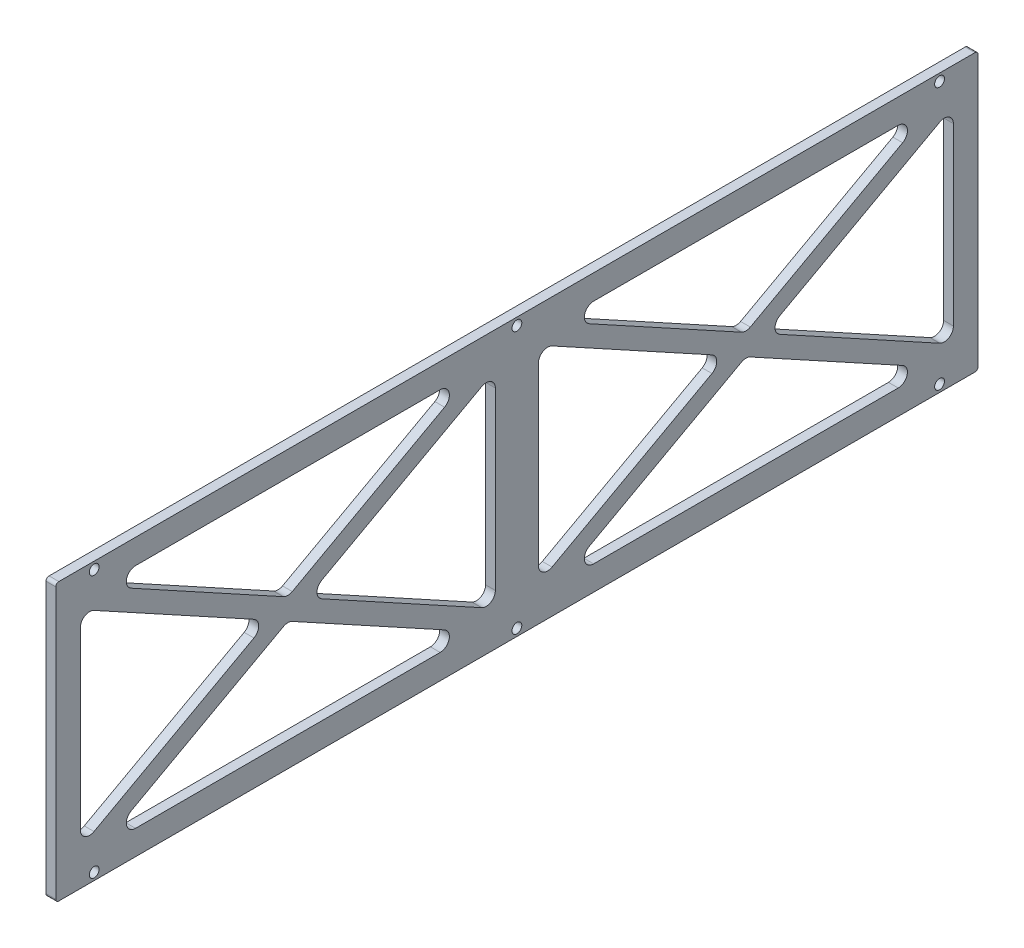
SolidWorks part; units mm, degrees
material "6061 Alloy"
ref_plane "Front Plane" through (0, 0, 0) normal (0, 0, 1) x (1, 0, 0)
ref_plane "Top Plane" through (0, 0, 0) normal (0, 1, 0) x (1, 0, 0)
ref_plane "Right Plane" through (0, 0, 0) normal (1, 0, 0) x (0, 0, -1)
sketch "Sketch2" plane through (0, 0, 0) normal (1, 0, 0) x (0, 0, -1)
  line L1 (-150, -45) -> (150, -45)
  line L2 (-150, -45) -> (-150, 45)
  line L3 (-150, 45) -> (150, 45)
  line L4 (150, -45) -> (150, 45)
  line L5 (-150, -45) -> (150, 45) construction
  line L6 (-150, 45) -> (150, -45) construction
  point P0 (0, 0)
  dimension "D1" = 300
  dimension "D2" = 90
extrude "Boss-Extrude1" add sketch "Sketch2" along normal blind 3.175
sketch "Sketch4" plane through (3.175, 0, 0) normal (1, 0, 0) x (0, 0, -1)
  line L0 (-150, 0) -> (-142, 0) construction
  line L1 (-142, -37) -> (-7, -37) construction
  line L2 (-142, -37) -> (-142, 37) construction
  line L3 (-142, 37) -> (-7, 37) construction
  line L4 (-7, -37) -> (-7, 37) construction
  line L5 (-142, -37) -> (-7, 37) construction
  line L6 (-142, 37) -> (-7, -37) construction
  line L7 (7, -37) -> (142, -37) construction
  line L8 (7, -37) -> (7, 37) construction
  line L9 (7, 37) -> (142, 37) construction
  line L10 (142, -37) -> (142, 37) construction
  line L11 (7, -37) -> (142, 37) construction
  line L12 (7, 37) -> (142, -37) construction
  line L13 (-150, 45) -> (-150, -45) construction
  line L14 (142, 0) -> (150, 0) construction
  line L15 (150, -45) -> (150, 45) construction
  line L17 (-143.442, 34.3693) -> (-8.442, -39.6307) construction
  line L18 (-142, 37) -> (-142, 45) construction
  line L19 (150, 45) -> (-150, 45) construction
  line L20 (-140.558, -39.6307) -> (-5.558, 34.3693) construction
  line L21 (-140.558, 39.6307) -> (-5.558, -34.3693) construction
  line L22 (-143.442, -34.3693) -> (-8.442, 39.6307) construction
  line L23 (-135.7587, 37) -> (-13.2413, 37)
  line L24 (-7, 33.5789) -> (-7, -33.5789)
  line L25 (-13.2413, -37) -> (-135.7587, -37)
  line L26 (-142, -33.5789) -> (-142, 33.5789)
  line L27 (-142, 33.5789) -> (-80.7413, 0)
  line L28 (-80.7413, 0) -> (-142, -33.5789)
  line L29 (-135.7587, -37) -> (-74.5, -3.4211)
  line L30 (-74.5, -3.4211) -> (-13.2413, -37)
  line L31 (-7, -33.5789) -> (-68.2587, 0)
  line L32 (-68.2587, 0) -> (-7, 33.5789)
  line L33 (-13.2413, 37) -> (-74.5, 3.4211)
  line L34 (-74.5, 3.4211) -> (-135.7587, 37)
  line L35 (5.558, 34.3693) -> (140.558, -39.6307) construction
  line L36 (8.442, -39.6307) -> (143.442, 34.3693) construction
  line L37 (8.442, 39.6307) -> (143.442, -34.3693) construction
  line L38 (5.558, -34.3693) -> (140.558, 39.6307) construction
  line L39 (135.7587, 37) -> (13.2413, 37)
  line L40 (13.2413, 37) -> (74.5, 3.4211)
  line L41 (74.5, 3.4211) -> (135.7587, 37)
  line L42 (142, 33.5789) -> (80.7413, 0)
  line L43 (80.7413, 0) -> (142, -33.5789)
  line L44 (142, -33.5789) -> (142, 33.5789)
  line L45 (135.7587, -37) -> (74.5, -3.4211)
  line L46 (74.5, -3.4211) -> (13.2413, -37)
  line L47 (13.2413, -37) -> (135.7587, -37)
  line L48 (7, -33.5789) -> (68.2587, 0)
  line L49 (68.2587, 0) -> (7, 33.5789)
  line L50 (7, 33.5789) -> (7, -33.5789)
  point P0 (-74.5, 0)
  point P5 (74.5, 0)
  dimension "D1" = 8
  dimension "D6" = 135
  dimension "D7" = 135
  dimension "D2" = 3
  dimension "D3" = 3
  dimension "D4" = 3
  dimension "D5" = 3
extrude "Cut-Extrude2" cut sketch "Sketch4" against normal through all
sketch "Sketch10" plane through (3.175, 0, 0) normal (1, 0, 0) x (0, 0, -1)
  line L0 (150, 45) -> (-150, 45) construction
  line L1 (-137.5, -42.6187) -> (137.5, -42.6187) construction
  line L2 (-137.5, -42.6187) -> (-137.5, 42.6187) construction
  line L3 (-137.5, 42.6187) -> (137.5, 42.6187) construction
  line L4 (137.5, -42.6187) -> (137.5, 42.6187) construction
  line L5 (-137.5, -42.6187) -> (137.5, 42.6187) construction
  line L6 (-137.5, 42.6187) -> (137.5, -42.6187) construction
  point P0 (0, 0)
  dimension "D1" = 2.3813
  dimension "D2" = 275
hole_wizard "M3 Clearance Hole1" positions "Sketch11" profile "Sketch12" hole size "M3" standard "ANSI Metric" end condition through all
sketch "Sketch11" plane through (3.175, 0, 0) normal (1, 0, 0) x (0, 0, -1)
  line L0 (-137.5, 42.6187) -> (137.5, 42.6187) construction
  line L1 (-137.5, -42.6187) -> (137.5, -42.6187) construction
  point P0 (-137.5, 42.6187)
  point P3 (137.5, 42.6187)
  point P6 (137.5, -42.6187)
  point P9 (-137.5, -42.6187)
  point P13 (0, 42.6188)
  point P17 (0, -42.6188)
sketch "Sketch12" plane through (3.175, 42.6187, 137.5) normal (0, 1, 0) x (0, 0, -1)
  line L0 (0, 0) -> (0, 3.175)
  line L1 (0, 3.175) -> (1.6, 3.175)
  line L2 (1.6, 3.175) -> (1.6, 0)
  line L5 (1.6, 0) -> (0, 0)
  line L11 (0, -6.35) -> (0, 107.95) construction
  dimension "Thru Hole Dia." = 3.2
  dimension "Thru Hole Depth" = 3.175
fillet "Fillet1" radius 3 24 edges at (1.5875, -37, -13.2413) (1.5875, -37, -135.7587) (1.5875, -3.4211, -74.5) (1.5875, -33.5789, -142) (1.5875, 33.5789, -142) (1.5875, 0, -80.7413) (1.5875, 37, -13.2413) (1.5875, 37, -135.7587) (1.5875, 3.4211, -74.5) (1.5875, 33.5789, -7) (1.5875, 0, -68.2587) (1.5875, -33.5789, -7) (1.5875, 37, 135.7587) (1.5875, 37, 13.2413) (1.5875, 3.4211, 74.5) (1.5875, 33.5789, 7) (1.5875, -33.5789, 7) (1.5875, 0, 68.2587) (1.5875, -37, 13.2413) (1.5875, -3.4211, 74.5) (1.5875, -37, 135.7587) (1.5875, 33.5789, 142) (1.5875, 0, 80.7413) (1.5875, -33.5789, 142)
fillet "Fillet2" radius 1 4 edges at (1.5875, -45, -150) (1.5875, -45, 150) (1.5875, 45, 150) (1.5875, 45, -150)
